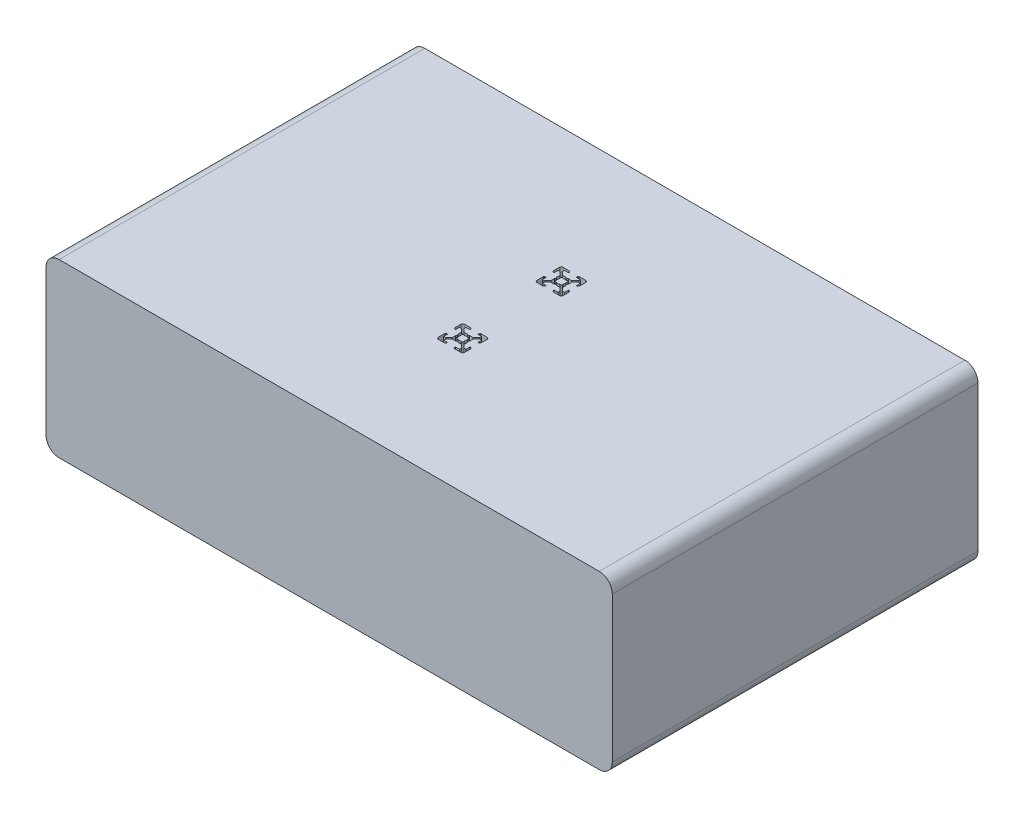
SolidWorks part; units mm, degrees
material "PE haute densité"
ref_plane "Plan de face" through (0, 0, 0) normal (0, 0, 1) x (1, 0, 0)
ref_plane "Plan de dessus" through (0, 0, 0) normal (0, 1, 0) x (1, 0, 0)
ref_plane "Plan de droite" through (0, 0, 0) normal (1, 0, 0) x (0, 0, -1)
sketch "Esquisse1" plane through (0, 0, 0) normal (0, 1, 0) x (1, 0, 0)
  line L1 (-216, 139.5) -> (216, 139.5)
  line L2 (-216, 139.5) -> (-216, -139.5)
  line L3 (-216, -139.5) -> (216, -139.5)
  line L4 (216, 139.5) -> (216, -139.5)
  line L5 (-216, 139.5) -> (216, -139.5) construction
  line L6 (-216, -139.5) -> (216, 139.5) construction
  point P0 (0, 0)
  dimension "D1" = 432
  dimension "D2" = 279
extrude "Boss.-Extru.1" add sketch "Esquisse1" along normal blind 131
fillet "Congé1" radius 10 4 edges at (-216, 0, 0) (-216, 131, 0) (216, 0, 0) (216, 131, 0)
sketch "Esquisse2" plane through (0, 131, 0) normal (0, 1, 0) x (1, 0, 0)
  circle A0 centre (0, 0) radius 25
  dimension "D1" = 50
sketch "Esquisse3" plane through (0, 131, 0) normal (0, 1, 0) x (1, 0, 0)
  line L0 (0, 0) -> (0, -37.6) construction
  line L79 (0, 0) -> (0, 37.6) construction
  line B0 (-3.0009, 39.5496) -> (-2.4359, 38.8763)
  line B1 (-2.4375, 36.3268) -> (-3.0032, 35.6527)
  line B2 (-3.0032, 35.6527) -> (-1.9496, 34.5991)
  line B3 (-1.9496, 34.5991) -> (-1.2763, 35.1641)
  line B4 (1.2732, 35.1625) -> (1.9473, 34.5968)
  line B5 (1.9473, 34.5968) -> (3.0009, 35.6504)
  line B6 (3.0009, 35.6504) -> (2.4359, 36.3237)
  line B7 (2.4375, 38.8732) -> (3.0032, 39.5473)
  line B8 (3.0032, 39.5473) -> (1.9496, 40.6009)
  line B9 (1.9496, 40.6009) -> (1.2763, 40.0359)
  line B10 (-1.2732, 40.0375) -> (-1.9473, 40.6032)
  line B11 (-1.9473, 40.6032) -> (-3.0009, 39.5496)
  line B12 (-10, 34.1) -> (-10, 29.1)
  line B13 (-8.5, 27.6) -> (-3.5, 27.6)
  line B14 (-3.5, 27.6) -> (-3.5, 28.1)
  line B15 (-3.5, 28.1) -> (-3, 28.1)
  line B16 (-3, 28.1) -> (-3, 29.1)
  line B17 (-3, 29.1) -> (-6, 29.1)
  line B18 (-6, 29.1) -> (-6, 30.5393)
  line B19 (-6, 30.5393) -> (-3.4393, 33.1)
  line B20 (-3.4393, 33.1) -> (-0.866, 33.1)
  line B21 (-0.866, 33.1) -> (0, 33.6)
  line B22 (0, 33.6) -> (0.866, 33.1)
  line B23 (0.866, 33.1) -> (3.4393, 33.1)
  line B24 (3.4393, 33.1) -> (6, 30.5393)
  line B25 (6, 30.5393) -> (6, 29.1)
  line B26 (6, 29.1) -> (3, 29.1)
  line B27 (3, 29.1) -> (3, 28.1)
  line B28 (3, 28.1) -> (3.5, 28.1)
  line B29 (3.5, 28.1) -> (3.5, 27.6)
  line B30 (3.5, 27.6) -> (8.5, 27.6)
  line B31 (10, 29.1) -> (10, 34.1)
  line B32 (10, 34.1) -> (9.5, 34.1)
  line B33 (9.5, 34.1) -> (9.5, 34.6)
  line B34 (9.5, 34.6) -> (8.5, 34.6)
  line B35 (8.5, 34.6) -> (8.5, 31.6)
  line B36 (8.5, 31.6) -> (7.0607, 31.6)
  line B37 (7.0607, 31.6) -> (4.5, 34.1607)
  line B38 (4.5, 34.1607) -> (4.5, 36.734)
  line B39 (4.5, 36.734) -> (4, 37.6)
  line B40 (4, 37.6) -> (4.5, 38.466)
  line B41 (4.5, 38.466) -> (4.5, 41.0393)
  line B42 (4.5, 41.0393) -> (7.0607, 43.6)
  line B43 (7.0607, 43.6) -> (8.5, 43.6)
  line B44 (8.5, 43.6) -> (8.5, 40.6)
  line B45 (8.5, 40.6) -> (9.5, 40.6)
  line B46 (9.5, 40.6) -> (9.5, 41.1)
  line B47 (9.5, 41.1) -> (10, 41.1)
  line B48 (10, 41.1) -> (10, 46.1)
  line B49 (8.5, 47.6) -> (3.5, 47.6)
  line B50 (3.5, 47.6) -> (3.5, 47.1)
  line B51 (3.5, 47.1) -> (3, 47.1)
  line B52 (3, 47.1) -> (3, 46.1)
  line B53 (3, 46.1) -> (6, 46.1)
  line B54 (6, 46.1) -> (6, 44.6607)
  line B55 (6, 44.6607) -> (3.4393, 42.1)
  line B56 (3.4393, 42.1) -> (0.866, 42.1)
  line B57 (0.866, 42.1) -> (0, 41.6)
  line B58 (0, 41.6) -> (-0.866, 42.1)
  line B59 (-0.866, 42.1) -> (-3.4393, 42.1)
  line B60 (-3.4393, 42.1) -> (-6, 44.6607)
  line B61 (-6, 44.6607) -> (-6, 46.1)
  line B62 (-6, 46.1) -> (-3, 46.1)
  line B63 (-3, 46.1) -> (-3, 47.1)
  line B64 (-3, 47.1) -> (-3.5, 47.1)
  line B65 (-3.5, 47.1) -> (-3.5, 47.6)
  line B66 (-3.5, 47.6) -> (-8.5, 47.6)
  line B67 (-10, 46.1) -> (-10, 41.1)
  line B68 (-10, 41.1) -> (-9.5, 41.1)
  line B69 (-9.5, 41.1) -> (-9.5, 40.6)
  line B70 (-9.5, 40.6) -> (-8.5, 40.6)
  line B71 (-8.5, 40.6) -> (-8.5, 43.6)
  line B72 (-8.5, 43.6) -> (-7.0607, 43.6)
  line B73 (-7.0607, 43.6) -> (-4.5, 41.0393)
  line B74 (-4.5, 41.0393) -> (-4.5, 38.466)
  line B75 (-4.5, 38.466) -> (-4, 37.6)
  line B76 (-4, 37.6) -> (-4.5, 36.734)
  line B77 (-4.5, 36.734) -> (-4.5, 34.1607)
  line B78 (-4.5, 34.1607) -> (-7.0607, 31.6)
  line B79 (-7.0607, 31.6) -> (-8.5, 31.6)
  line B80 (-8.5, 31.6) -> (-8.5, 34.6)
  line B81 (-8.5, 34.6) -> (-9.5, 34.6)
  line B82 (-9.5, 34.6) -> (-9.5, 34.1)
  line B83 (-9.5, 34.1) -> (-10, 34.1)
  arc B84 (-10, 29.1) -> (-8.5, 27.6) centre (-8.5, 29.1) ccw
  arc B85 (8.5, 27.6) -> (10, 29.1) centre (8.5, 29.1) ccw
  arc B86 (10, 46.1) -> (8.5, 47.6) centre (8.5, 46.1) ccw
  arc B87 (-8.5, 47.6) -> (-10, 46.1) centre (-8.5, 46.1) ccw
  arc B88 (-2.4359, 38.8763) -> (-2.4375, 36.3268) centre (0, 37.6) ccw
  arc B89 (-1.2763, 35.1641) -> (1.2732, 35.1625) centre (0, 37.6) ccw
  arc B90 (2.4359, 36.3237) -> (2.4375, 38.8732) centre (0, 37.6) ccw
  arc B91 (1.2763, 40.0359) -> (-1.2732, 40.0375) centre (0, 37.6) ccw
  line B92 (-3.0009, -35.6504) -> (-2.4359, -36.3237)
  line B93 (-2.4375, -38.8732) -> (-3.0032, -39.5473)
  line B94 (-3.0032, -39.5473) -> (-1.9496, -40.6009)
  line B95 (-1.9496, -40.6009) -> (-1.2763, -40.0359)
  line B96 (1.2732, -40.0375) -> (1.9473, -40.6032)
  line B97 (1.9473, -40.6032) -> (3.0009, -39.5496)
  line B98 (3.0009, -39.5496) -> (2.4359, -38.8763)
  line B99 (2.4375, -36.3268) -> (3.0032, -35.6527)
  line B100 (3.0032, -35.6527) -> (1.9496, -34.5991)
  line B101 (1.9496, -34.5991) -> (1.2763, -35.1641)
  line B102 (-1.2732, -35.1625) -> (-1.9473, -34.5968)
  line B103 (-1.9473, -34.5968) -> (-3.0009, -35.6504)
  line B104 (-10, -41.1) -> (-10, -46.1)
  line B105 (-8.5, -47.6) -> (-3.5, -47.6)
  line B106 (-3.5, -47.6) -> (-3.5, -47.1)
  line B107 (-3.5, -47.1) -> (-3, -47.1)
  line B108 (-3, -47.1) -> (-3, -46.1)
  line B109 (-3, -46.1) -> (-6, -46.1)
  line B110 (-6, -46.1) -> (-6, -44.6607)
  line B111 (-6, -44.6607) -> (-3.4393, -42.1)
  line B112 (-3.4393, -42.1) -> (-0.866, -42.1)
  line B113 (-0.866, -42.1) -> (0, -41.6)
  line B114 (0, -41.6) -> (0.866, -42.1)
  line B115 (0.866, -42.1) -> (3.4393, -42.1)
  line B116 (3.4393, -42.1) -> (6, -44.6607)
  line B117 (6, -44.6607) -> (6, -46.1)
  line B118 (6, -46.1) -> (3, -46.1)
  line B119 (3, -46.1) -> (3, -47.1)
  line B120 (3, -47.1) -> (3.5, -47.1)
  line B121 (3.5, -47.1) -> (3.5, -47.6)
  line B122 (3.5, -47.6) -> (8.5, -47.6)
  line B123 (10, -46.1) -> (10, -41.1)
  line B124 (10, -41.1) -> (9.5, -41.1)
  line B125 (9.5, -41.1) -> (9.5, -40.6)
  line B126 (9.5, -40.6) -> (8.5, -40.6)
  line B127 (8.5, -40.6) -> (8.5, -43.6)
  line B128 (8.5, -43.6) -> (7.0607, -43.6)
  line B129 (7.0607, -43.6) -> (4.5, -41.0393)
  line B130 (4.5, -41.0393) -> (4.5, -38.466)
  line B131 (4.5, -38.466) -> (4, -37.6)
  line B132 (4, -37.6) -> (4.5, -36.734)
  line B133 (4.5, -36.734) -> (4.5, -34.1607)
  line B134 (4.5, -34.1607) -> (7.0607, -31.6)
  line B135 (7.0607, -31.6) -> (8.5, -31.6)
  line B136 (8.5, -31.6) -> (8.5, -34.6)
  line B137 (8.5, -34.6) -> (9.5, -34.6)
  line B138 (9.5, -34.6) -> (9.5, -34.1)
  line B139 (9.5, -34.1) -> (10, -34.1)
  line B140 (10, -34.1) -> (10, -29.1)
  line B141 (8.5, -27.6) -> (3.5, -27.6)
  line B142 (3.5, -27.6) -> (3.5, -28.1)
  line B143 (3.5, -28.1) -> (3, -28.1)
  line B144 (3, -28.1) -> (3, -29.1)
  line B145 (3, -29.1) -> (6, -29.1)
  line B146 (6, -29.1) -> (6, -30.5393)
  line B147 (6, -30.5393) -> (3.4393, -33.1)
  line B148 (3.4393, -33.1) -> (0.866, -33.1)
  line B149 (0.866, -33.1) -> (0, -33.6)
  line B150 (0, -33.6) -> (-0.866, -33.1)
  line B151 (-0.866, -33.1) -> (-3.4393, -33.1)
  line B152 (-3.4393, -33.1) -> (-6, -30.5393)
  line B153 (-6, -30.5393) -> (-6, -29.1)
  line B154 (-6, -29.1) -> (-3, -29.1)
  line B155 (-3, -29.1) -> (-3, -28.1)
  line B156 (-3, -28.1) -> (-3.5, -28.1)
  line B157 (-3.5, -28.1) -> (-3.5, -27.6)
  line B158 (-3.5, -27.6) -> (-8.5, -27.6)
  line B159 (-10, -29.1) -> (-10, -34.1)
  line B160 (-10, -34.1) -> (-9.5, -34.1)
  line B161 (-9.5, -34.1) -> (-9.5, -34.6)
  line B162 (-9.5, -34.6) -> (-8.5, -34.6)
  line B163 (-8.5, -34.6) -> (-8.5, -31.6)
  line B164 (-8.5, -31.6) -> (-7.0607, -31.6)
  line B165 (-7.0607, -31.6) -> (-4.5, -34.1607)
  line B166 (-4.5, -34.1607) -> (-4.5, -36.734)
  line B167 (-4.5, -36.734) -> (-4, -37.6)
  line B168 (-4, -37.6) -> (-4.5, -38.466)
  line B169 (-4.5, -38.466) -> (-4.5, -41.0393)
  line B170 (-4.5, -41.0393) -> (-7.0607, -43.6)
  line B171 (-7.0607, -43.6) -> (-8.5, -43.6)
  line B172 (-8.5, -43.6) -> (-8.5, -40.6)
  line B173 (-8.5, -40.6) -> (-9.5, -40.6)
  line B174 (-9.5, -40.6) -> (-9.5, -41.1)
  line B175 (-9.5, -41.1) -> (-10, -41.1)
  arc B176 (-10, -46.1) -> (-8.5, -47.6) centre (-8.5, -46.1) ccw
  arc B177 (8.5, -47.6) -> (10, -46.1) centre (8.5, -46.1) ccw
  arc B178 (10, -29.1) -> (8.5, -27.6) centre (8.5, -29.1) ccw
  arc B179 (-8.5, -27.6) -> (-10, -29.1) centre (-8.5, -29.1) ccw
  arc B180 (-2.4359, -36.3237) -> (-2.4375, -38.8732) centre (0, -37.6) ccw
  arc B181 (-1.2763, -40.0359) -> (1.2732, -40.0375) centre (0, -37.6) ccw
  arc B182 (2.4359, -38.8763) -> (2.4375, -36.3268) centre (0, -37.6) ccw
  arc B183 (1.2763, -35.1641) -> (-1.2732, -35.1625) centre (0, -37.6) ccw
  dimension "D1" = 37.6
  dimension "125" = 37.6
sketch_block_instance "Bloc1-1"
sketch_block "Bloc1"
sketch_block_instance "Bloc1-3"
extrude "Enlèv. mat.-Extru.2" cut sketch "Esquisse3" against normal blind 100
